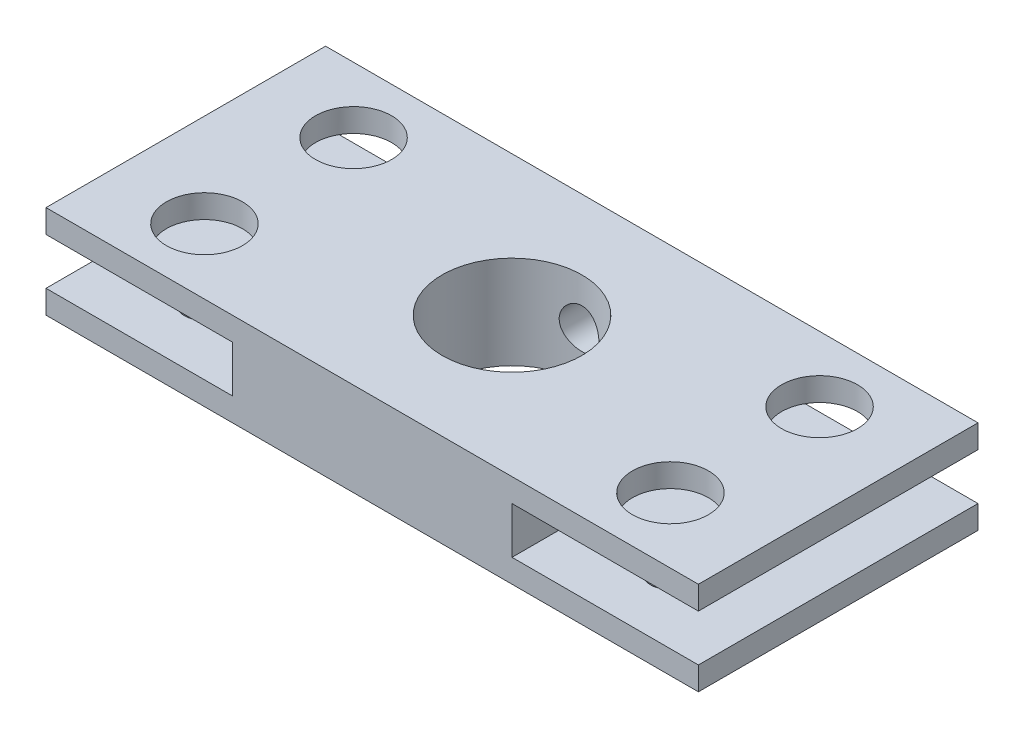
SolidWorks part; units mm, degrees
ref_plane "Front Plane" through (0, 0, 0) normal (0, 0, 1) x (1, 0, 0)
ref_plane "Top Plane" through (0, 0, 0) normal (0, 1, 0) x (1, 0, 0)
ref_plane "Right Plane" through (0, 0, 0) normal (1, 0, 0) x (0, 0, -1)
sketch "Sketch1" plane through (0, 0, 0) normal (0, 1, 0) x (1, 0, 0)
  line L21 (-22.225, -9.525) -> (22.225, -9.525)
  line L22 (-22.225, -9.525) -> (-22.225, 9.525)
  line L23 (-22.225, 9.525) -> (22.225, 9.525)
  line L24 (22.225, -9.525) -> (22.225, 9.525)
  line L25 (-22.225, -9.525) -> (22.225, 9.525) construction
  line L26 (-22.225, 9.525) -> (22.225, -9.525) construction
  circle A5 centre (0, 0) radius 4.7625
  dimension "D1" = 9.525
  dimension "D2" = 44.45
  dimension "D3" = 19.05
extrude "Boss-Extrude1" add sketch "Sketch1" along normal blind 6.35
sketch "Sketch2" plane through (0, 0, -9.525) normal (0, 0, -1) x (-1, 0, 0)
  line L3 (0, 3.4925) -> (0, -3.4925) construction
  line L4 (-22.225, 6.35) -> (-22.225, 0) construction
  point P0 (0, 3.175)
  point P1 (0, 0)
  point P2 (0, 0)
  point P5 (0, 0)
  point P8 (-22.225, 3.175)
  point P9 (0, 0)
  point P10 (0, 0)
hole_wizard "#6-32 Tapped Hole1" positions "Sketch3" profile "Sketch4" tap size "#6-32" standard "ANSI Inch"
sketch "Sketch3" plane through (0, 0, -9.525) normal (0, 0, -1) x (-1, 0, 0)
  point P0 (0, 3.175)
sketch "Sketch4" plane through (0, 3.175, -9.525) normal (1, 0, 0) x (0, 1, 0)
  line L0 (0, 0) -> (0, 4.7625)
  line L1 (0, 4.7625) -> (1.3525, 4.7625)
  line L2 (1.3525, 4.7625) -> (1.3525, 0)
  line L5 (1.3525, 0) -> (0, 0)
  line L11 (0, -6.35) -> (0, 107.95) construction
  dimension "Thru Tap Drill Dia." = 2.7051
  dimension "Thru Tap Drill Depth" = 4.7625
cosmetic thread "Hole Thread7" parameters "D1"=4.6318, "D2"=3.7051
sketch "Sketch5" [suppressed] plane through (9.525, 0, 0) normal (1, 0, 0) x (0, 0, -1)
  line L0 (0, 55) -> (0, -55) construction
  point P0 (0, 3.175)
hole_wizard "#6-32 Tapped Hole2" [suppressed] positions "Sketch6" profile "Sketch7" tap size "#6-32" standard "ANSI Inch"
sketch "Sketch6" [suppressed] plane through (9.525, 0, 0) normal (1, 0, 0) x (0, 0, -1)
  point P0 (0, 3.175)
sketch "Sketch7" plane through (9.525, 3.175, 0) normal (0, 1, 0) x (0, 0, -1)
  line L0 (0, 0) -> (0, 4.7625)
  line L1 (0, 4.7625) -> (1.3525, 4.7625)
  line L2 (1.3525, 4.7625) -> (1.3525, 0)
  line L5 (1.3525, 0) -> (0, 0)
  line L11 (0, -6.35) -> (0, 107.95) construction
  dimension "Thru Tap Drill Dia." = 2.7051
  dimension "Thru Tap Drill Depth" = 4.7625
cosmetic thread "Hole Thread2" [suppressed] parameters "D2"=3.5052
sketch "Sketch8" [suppressed] plane through (9.525, 0, 0) normal (1, 0, 0) x (0, 0, -1)
  line L0 (-9.525, 6.35) -> (-9.525, 0) construction
  point P0 (-5.715, 3.175)
  point P5 (-9.525, 3.175)
  dimension "D1" = 3.81
hole_wizard "#6-32 Tapped Hole3" [suppressed] positions "Sketch9" profile "Sketch11" tap size "#6-32" standard "ANSI Inch"
sketch "Sketch9" [suppressed] plane through (9.525, 0, 0) normal (1, 0, 0) x (0, 0, -1)
  point P0 (-5.715, 3.175)
sketch "Sketch11" plane through (9.525, 3.175, 5.715) normal (0, 1, 0) x (0, 0, -1)
  line L0 (0, 0) -> (0, 6.35)
  line L1 (0, 6.35) -> (1.3525, 5.5373)
  line L2 (1.3525, 5.5373) -> (1.3525, 0)
  line L5 (1.3525, 0) -> (0, 0)
  line L10 (0, 6.35) -> (-1.3526, 5.5373) construction
  line L11 (0, -6.35) -> (0, 107.95) construction
  dimension "Tap Drill Dia." = 2.7051
  dimension "Tap Drill Depth" = 6.35
  dimension "Drill Angle" = 118
cosmetic thread "Hole Thread3" [suppressed] parameters "D1"=5.588, "D2"=3.5052
mirror "Mirror1" [suppressed] about plane through (0, 0, 0) normal (0, 0, 1)
cosmetic thread "Hole Thread4" [suppressed] parameters "D1"=5.588, "D2"=3.5052
mirror "Mirror2" [suppressed] about plane through (0, 0, 0) normal (1, 0, 0)
cosmetic thread "Hole Thread5" [suppressed] parameters "D1"=5.588, "D2"=3.5052
cosmetic thread "Hole Thread6" [suppressed] parameters "D1"=5.588, "D2"=3.5052
sketch "Sketch15" plane through (0, 0, 9.525) normal (0, 0, 1) x (1, 0, 0)
  line L0 (22.225, 6.35) -> (22.225, 0) construction
  line L1 (9.525, 1.5875) -> (22.225, 1.5875)
  line L2 (9.525, 1.5875) -> (9.525, 4.7625)
  line L3 (9.525, 4.7625) -> (22.225, 4.7625)
  line L4 (22.225, 1.5875) -> (22.225, 4.7625)
  line L5 (9.525, 1.5875) -> (22.225, 4.7625) construction
  line L6 (9.525, 4.7625) -> (22.225, 1.5875) construction
  point P0 (15.875, 3.175)
  dimension "D1" = 3.175
  dimension "D2" = 12.7
extrude "Cut-Extrude1" cut sketch "Sketch15" against normal through all
sketch "Sketch12" plane through (0, 6.35, 0) normal (0, 1, 0) x (1, 0, 0)
  line L0 (15.875, 5.08) -> (15.875, -5.08) construction
  line L3 (-3.4925, 0) -> (3.4925, 0) construction
  line L4 (22.225, 9.525) -> (22.225, -9.525) construction
  point P0 (15.875, 5.08)
  point P1 (15.875, -5.08)
  point P4 (15.875, 0)
  dimension "D1" = 6.35
  dimension "D2" = 10.16
hole_wizard "#6 (0.204) Diameter Hole1" positions "Sketch13" profile "Sketch14" hole size "#6" standard "ANSI Inch"
sketch "Sketch13" plane through (0, 6.35, 0) normal (0, 1, 0) x (1, 0, 0)
  point P0 (15.875, 5.08)
  point P3 (15.875, -5.08)
sketch "Sketch14" plane through (15.875, 6.35, -5.08) normal (1, 0, 0) x (0, 0, 1)
  line L0 (0, 0) -> (0, 1.5875)
  line L1 (0, 1.5875) -> (2.5908, 1.5875)
  line L2 (2.5908, 1.5875) -> (2.5908, 0)
  line L5 (2.5908, 0) -> (0, 0)
  line L11 (0, -6.35) -> (0, 107.95) construction
  dimension "Thru Hole Dia." = 5.1816
  dimension "Thru Hole Depth" = 1.5875
hole_wizard "#6-32 Tapped Hole4" positions "Sketch16" profile "Sketch18" tap size "#6-32" standard "ANSI Inch" end condition up to next
sketch "Sketch16" plane through (0, 1.5875, 0) normal (0, 1, 0) x (1, 0, 0)
  point P0 (15.875, 5.08)
  point P3 (15.875, -5.08)
sketch "Sketch18" plane through (15.875, 1.5875, -5.08) normal (1, 0, 0) x (0, 0, 1)
  line L0 (0, 0) -> (0, 1.5875)
  line L1 (0, 1.5875) -> (1.3525, 1.5875)
  line L2 (1.3525, 1.5875) -> (1.3525, 0)
  line L5 (1.3525, 0) -> (0, 0)
  line L11 (0, -6.35) -> (0, 107.95) construction
  dimension "Thru Tap Drill Dia." = 2.7051
  dimension "Thru Tap Drill Depth" = 1.5875
cosmetic thread "Hole Thread8" parameters "D2"=3.5052
cosmetic thread "Hole Thread9" parameters "D2"=3.5052
mirror "Mirror3" about plane through (0, 0, 0) normal (1, 0, 0) of "#6-32 Tapped Hole4", "#6 (0.204) Diameter Hole1", "Cut-Extrude1"
cosmetic thread "Hole Thread10" parameters "D2"=3.5052
cosmetic thread "Hole Thread11" parameters "D2"=3.5052
sketch "Sketch19" plane through (0, 6.35, 0) normal (0, 1, 0) x (1, 0, 0)
  line L0 (-22.225, -9.525) -> (22.225, -9.525) construction
  line L1 (22.225, 9.525) -> (9.525, 9.525)
  line L2 (22.225, 9.525) -> (22.225, -4.445)
  line L3 (22.225, -4.445) -> (9.525, -4.445)
  line L4 (9.525, 9.525) -> (9.525, -4.445)
  line L5 (22.225, 9.525) -> (-22.225, 9.525) construction
  line L7 (22.225, -9.525) -> (22.225, 9.525) construction
  point P7 (0, 0)
  point P8 (19.5364, 9.525)
  dimension "D1" = 12.7
  dimension "D2" = 5.08
extrude "Cut-Extrude2" [suppressed] cut sketch "Sketch19" against normal through all
mirror "Mirror4" [suppressed] about plane through (0, 0, 0) normal (1, 0, 0)
